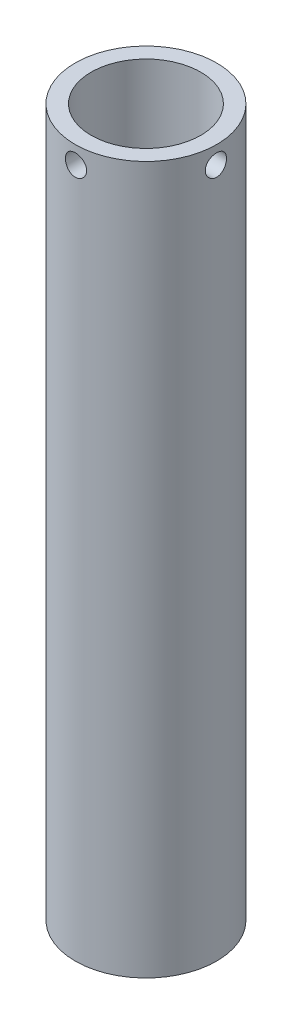
SolidWorks part; units mm, degrees
material "Brass"
ref_plane "Front Plane" through (0, 0, 0) normal (0, 0, 1) x (1, 0, 0)
ref_plane "Top Plane" through (0, 0, 0) normal (0, 1, 0) x (1, 0, 0)
ref_plane "Right Plane" through (0, 0, 0) normal (1, 0, 0) x (0, 0, -1)
sketch "Sketch1" plane through (0, 0, 0) normal (0, 1, 0) x (1, 0, 0)
  circle A0 centre (0, 0) radius 2
  circle A1 centre (0, 0) radius 1.55
  dimension "D1" = 4
  dimension "D2" = 0.45
extrude "Boss-Extrude1" add sketch "Sketch1" along normal blind 20 contours A1
hole_wizard "Ø0.6 (0.6) Diameter Hole1" positions "3DSketch1" profile "Sketch2" hole size "Ø0.6" standard "ANSI Metric"
sketch3d "3DSketch1"
  line L0 (0, 20, 0) -> (0, 19.5, 0) construction
  line L3 (0, 19.5, 0) -> (0, 19.5, 2) construction
  line L8 (0, 19.5, 0) -> (2, 19.5, 0) construction
  point P17 (2, 19.5, 0)
  point P19 (0, 19.5, 2)
  dimension "D1" = 0.5
sketch "Sketch2" plane through (2, 19.5, 0) normal (0, 1, 0) x (0, 0, -1)
  line L0 (0, 0) -> (0, 0.45)
  line L1 (0, 0.45) -> (0.3, 0.45)
  line L2 (0.3, 0.45) -> (0.3, 0)
  line L5 (0.3, 0) -> (0, 0)
  line L11 (0, -6.35) -> (0, 107.95) construction
  dimension "Thru Hole Dia." = 0.6
  dimension "Thru Hole Depth" = 0.45
